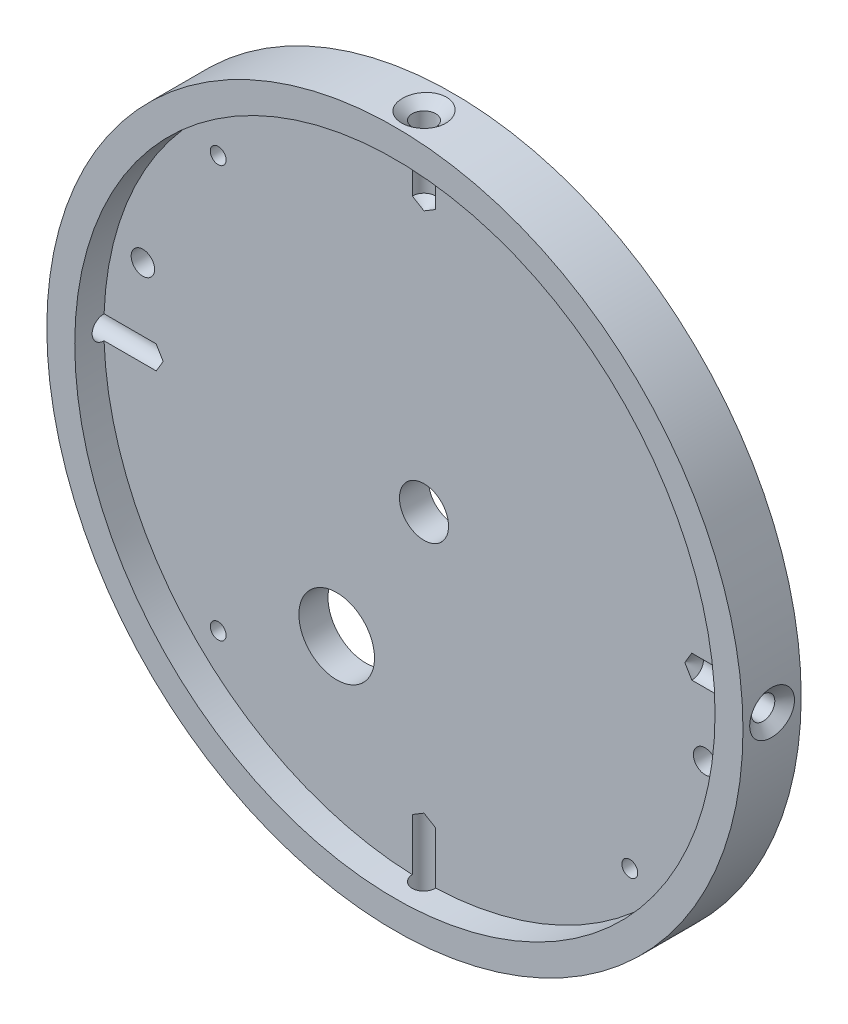
SolidWorks part; units mm, degrees
material "6061 Alloy"
ref_plane "Front Plane" through (0, 0, 0) normal (0, 0, 1) x (1, 0, 0)
ref_plane "Top Plane" through (0, 0, 0) normal (0, 1, 0) x (1, 0, 0)
ref_plane "Right Plane" through (0, 0, 0) normal (1, 0, 0) x (0, 0, -1)
sketch "Sketch1" plane through (0, 0, 0) normal (0, 0, 1) x (1, 0, 0)
  circle A0 centre (0, 0) radius 75.946
  dimension "D1" = 151.892
extrude "Boss-Extrude1" add sketch "Sketch1" along normal blind 12.7
sketch "Sketch2" plane through (0, 0, 12.7) normal (0, 0, 1) x (1, 0, 0)
  circle A0 centre (0, 0) radius 69.85
  dimension "D1" = 139.7
extrude "Cut-Extrude1" cut sketch "Sketch2" against normal blind 6.35
sketch "Sketch3" plane through (0, 0, 6.35) normal (0, 0, 1) x (1, 0, 0)
  line L0 (-19.05, -32.9956) -> (0, 0) construction
  line L1 (0, 0) -> (0, -69.85) construction
  line L2 (-61.3363, 16.435) -> (61.3363, -16.435) construction
  line L3 (0, 0) -> (-69.85, 0) construction
  line L4 (-44.9013, 44.9013) -> (44.9013, -44.9013) construction
  line L5 (-44.9013, -44.9013) -> (44.9013, 44.9013) construction
  circle A0 centre (0, 0) radius 5.3581
  circle A1 centre (-19.05, -32.9956) radius 8.25
  circle A2 centre (-61.3363, 16.435) radius 2.5527
  circle A3 centre (61.3363, -16.435) radius 2.5527
  circle A4 centre (44.9013, 44.9013) radius 1.7272
  circle A5 centre (-44.9013, 44.9013) radius 1.7272
  circle A6 centre (-44.9013, -44.9013) radius 1.7272
  circle A7 centre (44.9013, -44.9013) radius 1.7272
  circle A8 centre (0, 0) radius 69.85 construction
  circle A9 centre (0, 0) radius 69.85 construction
  dimension "D1" = 10.7163
  dimension "D2" = 16.5
  dimension "D3" = 5.1054
  dimension "D4" = 38.1
  dimension "D5" = 3.4544
  dimension "D6" = 30
  dimension "D8" = 63.5
  dimension "D7" = 15
  dimension "D9" = 63.5
  dimension "D10" = 45
extrude "Cut-Extrude2" cut sketch "Sketch3" against normal through all
ref_plane "Plane1" through (0, 75.946, 0) normal (0, 1, 0) x (1, 0, 0)
sketch "Sketch4" plane through (0, 75.946, 0) normal (0, 1, 0) x (1, 0, 0)
  line L0 (-75.946, 0) -> (75.946, -12.7) construction
  line L1 (-75.946, -12.7) -> (75.946, -12.7) construction
  line L2 (-75.946, -12.7) -> (-75.946, 0) construction
  line L3 (-75.946, 0) -> (75.946, 0) construction
  line L4 (75.946, -12.7) -> (75.946, 0) construction
  line L5 (75.946, 0) -> (-75.946, -12.7) construction
  point P0 (0, -6.35)
hole_wizard "CSK for #10 Flat Head Machine Screw (100)1" positions "Sketch4" profile "Sketch5" countersink size "#10" standard "ANSI Inch"
sketch "Sketch5" plane through (0, 75.946, 6.35) normal (1, 0, 0) x (0, 0, 1)
  line L0 (0, 0) -> (0, 19.05)
  line L1 (0, 19.05) -> (2.5527, 17.5162)
  line L2 (2.5527, 17.5162) -> (2.5527, 1.9608)
  line L3 (2.5527, 1.9608) -> (4.8895, 0)
  line L5 (4.8895, 0) -> (0, 0)
  line L6 (-2.5527, 1.9608) -> (-4.8895, 0) construction
  line L10 (0, 19.05) -> (-2.5527, 17.5162) construction
  line L11 (0, -6.35) -> (0, 107.95) construction
  dimension "Hole Dia." = 5.1054
  dimension "Hole Depth" = 19.05
  dimension "Near C'Sink Dia." = 9.779
  dimension "Near C'Sink Angle" = 100
  dimension "Drill Angle" = 118
pattern_circular "CirPattern1" count 4 over 360 about axis through (0, 0, 12.7) along (0, 0, 1) of "CSK for #10 Flat Head Machine Screw (100)1"
